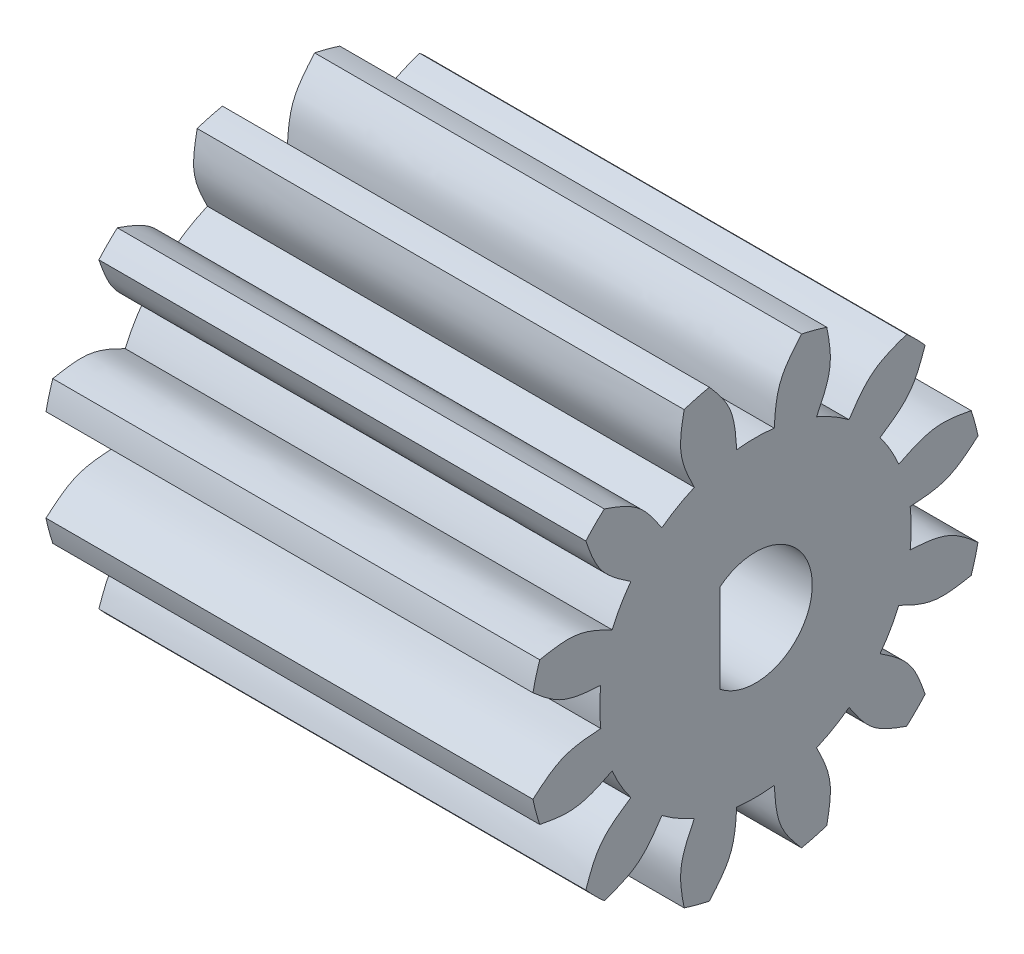
SolidWorks part; units mm, degrees
ref_plane "Front" through (0, 0, 0) normal (0, 0, 1) x (1, 0, 0)
ref_plane "Top" through (0, 0, 0) normal (0, 1, 0) x (1, 0, 0)
ref_plane "Right" through (0, 0, 0) normal (1, 0, 0) x (0, 0, -1)
sketch "Ritning 1" plane through (0, 0, 0) normal (0, 0, 1) x (1, 0, 0)
  line L0 (12.5, 1) -> (2.5, 1)
  line L1 (2.5, 1) -> (2.5, 3.5)
  line L2 (2.5, 3.5) -> (-12.5, 3.5)
  line L3 (12.5, 1) -> (12.5, -3.5)
  line L4 (-12.5, 3.5) -> (-12.5, -3.5)
  line L5 (-12.5, -3.5) -> (12.5, -3.5)
  dimension "D1" = 2.5
  dimension "D2" = 12.5
  dimension "D3" = 12.5
  dimension "D4" = 1
  dimension "D5" = 3.5
  dimension "D6" = 3.5
revolve "Kugghjulsämne" add sketch "Ritning 1" angle 360 about L5
sketch "Ritning 2" plane through (-12.5, 0, 0) normal (-1, 0, 0) x (0, 0, 1)
  line L0 (0, -3.5) -> (0, 3.5) construction
  line L1 (1.4199, 3.3545) -> (0, 4.7744)
  line L2 (-1.4199, 3.3545) -> (0, 4.7744)
  line L3 (0, -3.5) -> (1.4199, -3.5) construction
  arc A0 (0.5768, 1.2652) -> (-0.5768, 1.2652) centre (0, -3.5) ccw
  circle A1 centre (0, -3.5) radius 7 construction
  spline S0 degree 3 poles (1.4199, 3.3545) (1.173, 3.0671) (0.6581, 2.4675) (0.6046, 1.6769) (0.5768, 1.2652) knots 0 0 0 0 0.479362 1 1 1 1
  spline S1 degree 3 poles (-1.4199, 3.3545) (-1.173, 3.0671) (-0.6581, 2.4675) (-0.6046, 1.6769) (-0.5768, 1.2652) knots 0 0 0 0 0.479362 1 1 1 1
  dimension "D1" = 4.8
  dimension "D2" = 0.5768
  dimension "D3" = 0.7854
  dimension "D4" = 1.4199
  dimension "D5" = 5.9484
  dimension "D6" = 0.7854
  dimension "D7" = 6.8545
extrude "Kugglucka" cut sketch "Ritning 2" against normal up to surface (15 mm away) up to face at (2.5, -3.5, 7)
pattern_circular "CirPattern" count 12 over 360 about axis through (-12.5, -3.5, 0) along (-1, 0, 0) of "Kugglucka"
sketch "Sketch1" plane through (12.5, 0, 0) normal (1, 0, 0) x (0, 0, -1)
  circle A1 centre (0, -3.5) radius 4.5
  circle A2 centre (0, -3.5) radius 4.5
  dimension "D1" = 0
extrude "Cut-Extrude1" cut sketch "Sketch1" against normal up to surface (10 mm away) up to face at (2.5, -3.5, 0)
sketch "Sketch2" plane through (2.5, 0, 0) normal (1, 0, 0) x (0, 0, -1)
  line L0 (-1.1, -2.1389) -> (-1.1, -4.8611)
  arc A0 (-1.1, -4.8611) -> (-1.1, -2.1389) centre (0, -3.5) ccw
  dimension "D1" = 3.5
  dimension "D2" = 1.1
extrude "Cut-Extrude2" cut sketch "Sketch2" against normal blind 10
